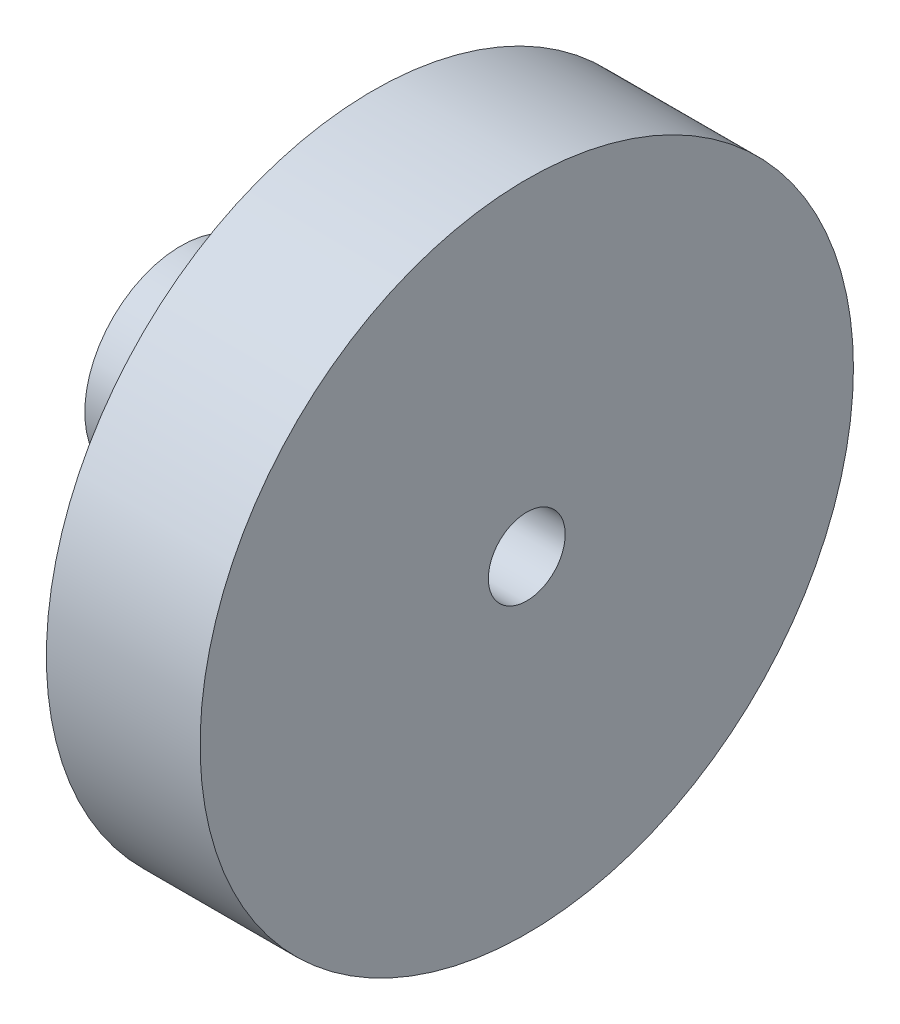
SolidWorks part; units mm, degrees
material "1.4401 (X5CrNiMo17-12-2)"
ref_plane "Plano frontal" through (0, 0, 0) normal (0, 0, 1) x (1, 0, 0)
ref_plane "Plano superior" through (0, 0, 0) normal (0, 1, 0) x (1, 0, 0)
ref_plane "Plano direito" through (0, 0, 0) normal (1, 0, 0) x (0, 0, -1)
sketch "Esboço3" plane through (0, 0, 0) normal (0, 0, 1) x (1, 0, 0)
  line L0 (0, 0) -> (-50.7324, 0) construction
  line L1 (0, 17) -> (0, 2)
  line L2 (0, 17) -> (-8, 17)
  line L3 (-8, 17) -> (-8, 5)
  line L4 (-8, 5) -> (-18, 5)
  line L5 (-18, 5) -> (-18, 2)
  line L6 (-18, 2) -> (0, 2)
  dimension "D1" = 2
  dimension "D2" = 17
  dimension "D3" = 8
  dimension "D4" = 10
  dimension "D5" = 5
revolve "Revolução1" add sketch "Esboço3" angle 360 about L0
ref_plane "Plano1" through (0, 5, 0) normal (0, 1, 0) x (1, 0, 0)
hole_wizard "Broca de rosquear para tarraxa de M2.2x0.451" positions "3DSketch6" profile "Esboço11" hole size "M2.2x0.45" standard "DIN"
sketch3d "3DSketch6"
  point P0 (-13.4532, 5, 0)
sketch "Esboço11" plane through (-13.4532, 5, 0) normal (1, 0, 0) x (0, 0, 1)
  line L0 (0, 0) -> (0, 3)
  line L1 (0, 3) -> (0.875, 3)
  line L2 (0.875, 3) -> (0.875, 0)
  line L5 (0.875, 0) -> (0, 0)
  line L11 (0, -6.35) -> (0, 107.95) construction
  dimension "Thru Hole Dia." = 1.75
  dimension "Thru Hole Depth" = 3
